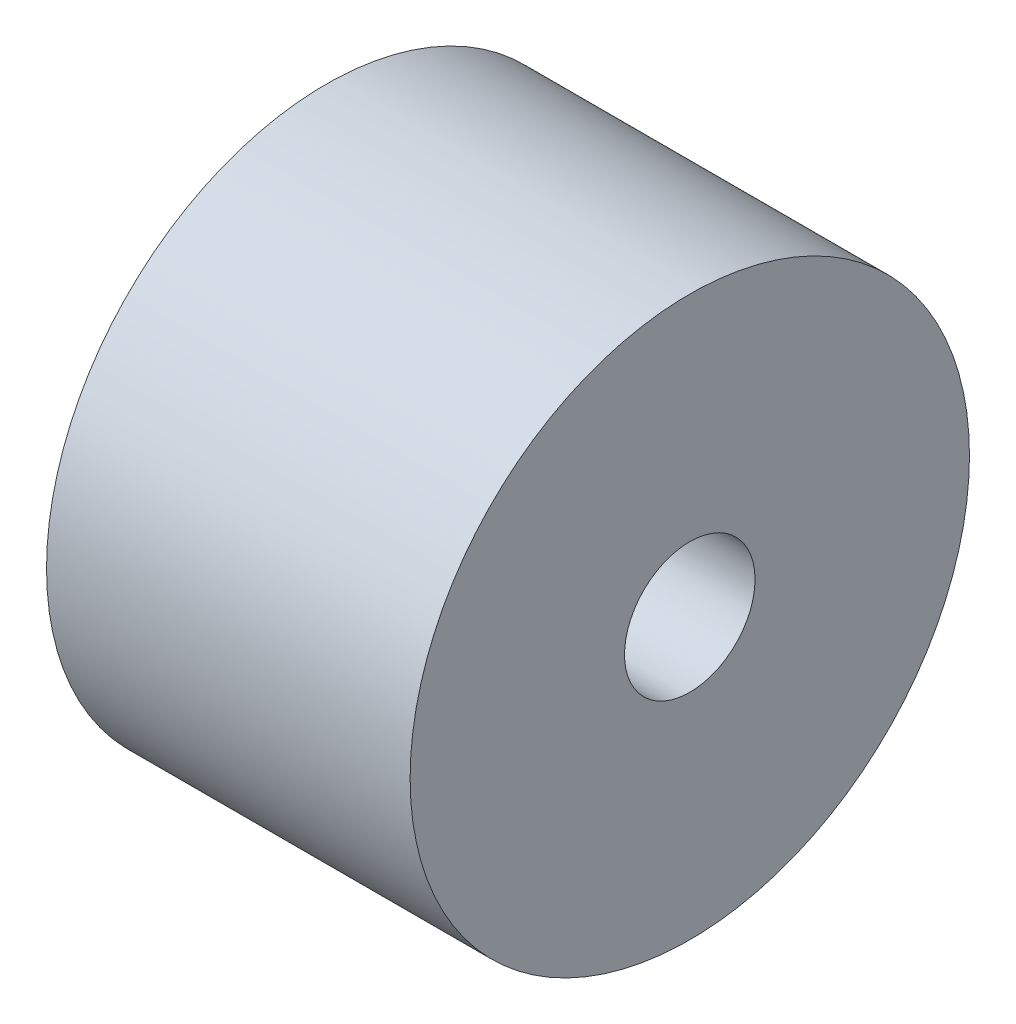
SolidWorks part; units mm, degrees
ref_plane "Front Plane" through (0, 0, 0) normal (0, 0, 1) x (1, 0, 0)
ref_plane "Top Plane" through (0, 0, 0) normal (0, 1, 0) x (1, 0, 0)
ref_plane "Right Plane" through (0, 0, 0) normal (1, 0, 0) x (0, 0, -1)
sketch "Sketch1" plane through (0, 0, 0) normal (1, 0, 0) x (0, 0, -1)
  circle A0 centre (0, 0) radius 2.1
  circle A1 centre (0, 0) radius 9
  dimension "D1" = 4.2
  dimension "D2" = 18
extrude "Boss-Extrude1" add sketch "Sketch1" along normal blind 11.7
